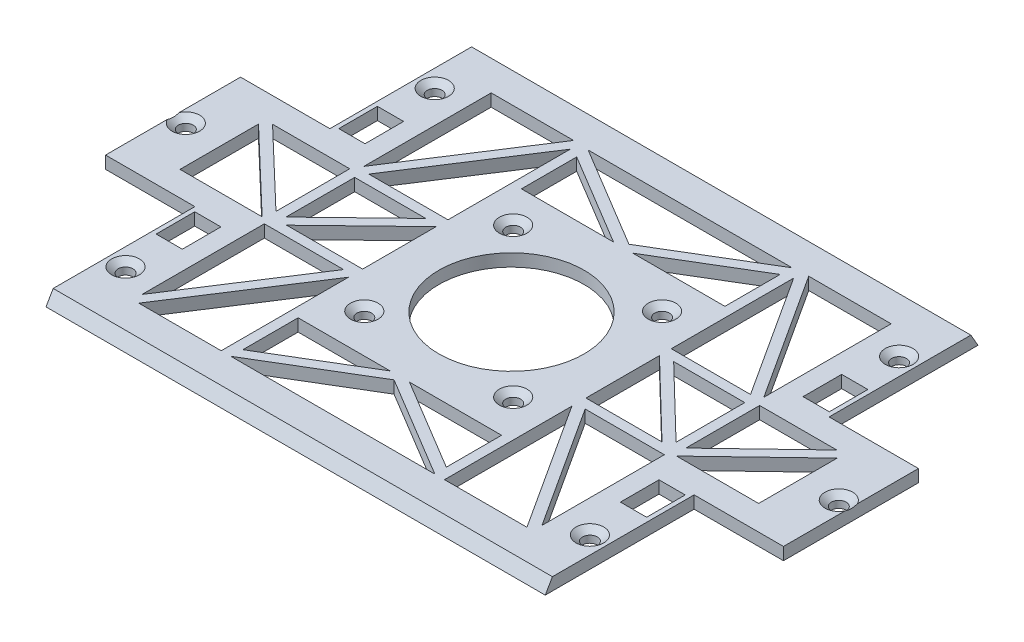
SolidWorks part; units mm, degrees
material "6061-T6 (SS)"
ref_plane "Front Plane" through (0, 0, 0) normal (0, 0, 1) x (1, 0, 0)
ref_plane "Top Plane" through (0, 0, 0) normal (0, 1, 0) x (1, 0, 0)
ref_plane "Right Plane" through (0, 0, 0) normal (1, 0, 0) x (0, 0, -1)
sketch "Sketch1" plane through (0, 0, 0) normal (0, 1, 0) x (1, 0, 0)
  line L0 (-65.4553, 70.6447) -> (62.3067, 70.6447)
  line L1 (62.3067, -40.0993) -> (-65.4553, -40.0993)
  line L2 (-65.4553, 70.6447) -> (-65.4553, 32.5447)
  line L4 (62.3067, 70.6447) -> (62.3067, 32.5447)
  line L9 (-65.4553, -1.9993) -> (-65.4553, -40.0993)
  line L11 (62.3067, 32.5447) -> (85.1667, 32.5447)
  line L13 (62.3067, -1.9993) -> (85.1667, -1.9993)
  line L14 (85.1667, 32.5447) -> (85.1667, -1.9993)
  line L15 (-65.4553, -1.9993) -> (-88.3153, -1.9993)
  line L17 (-65.4553, 32.5447) -> (-88.3153, 32.5447)
  line L18 (-88.3153, -1.9993) -> (-88.3153, 32.5447)
  line L19 (62.3067, -1.9993) -> (62.3067, -40.0993)
  circle A0 centre (-1.5743, 15.1457) radius 18.5801
  point P0 (0, 0)
  dimension "D5" = 63.881
  dimension "D7" = 62.3067
  dimension "D6" = 55.499
  dimension "D9" = 37.1602
  dimension "D1" = 127.762
  dimension "D2" = 38.1
  dimension "D3" = 34.544
  dimension "D4" = 22.86
  dimension "D8" = 15.1457
extrude "Boss-Extrude1" add sketch "Sketch1" along normal blind 3.175
ref_plane "Plane1" through (0, 0, -15.2727) normal (0, 0, 1) x (1, 0, 0)
hole_wizard "CSK for #6 Flat Head Machine Screw (100)1" positions "Sketch3" profile "Sketch2" countersink size "#6" standard "ANSI Inch" end condition through all
sketch "Sketch3" plane through (0, 3.175, 0) normal (0, 1, 0) x (1, 0, 0)
  point P0 (-60.9786, 54.8967)
  point P3 (-85.1086, 15.3362)
  point P6 (-60.9786, -24.2243)
  point P9 (57.8617, -24.2243)
  point P12 (81.9917, 15.3362)
  point P15 (57.8617, 54.8967)
  point P18 (-20.6085, 34.6084)
  point P21 (-20.6085, -3.4916)
  point P24 (17.4915, -3.4916)
  point P27 (17.4915, 34.6084)
sketch "Sketch2" plane through (-60.9786, 3.175, -54.8967) normal (1, 0, 0) x (0, 0, 1)
  line L0 (0, 0) -> (0, 3.175)
  line L1 (0, 3.175) -> (1.8986, 3.175)
  line L2 (1.8986, 3.175) -> (1.8986, 1.38)
  line L3 (1.8986, 1.38) -> (3.5433, 0)
  line L5 (3.5433, 0) -> (0, 0)
  line L6 (-1.8986, 1.38) -> (-3.5433, 0) construction
  line L11 (0, -6.35) -> (0, 107.95) construction
  dimension "Thru Hole Dia." = 3.7973
  dimension "Thru Hole Depth" = 3.175
  dimension "Near C'Sink Dia." = 7.0866
  dimension "Near C'Sink Angle" = 100
sketch "Sketch4" plane through (0, 0, 0) normal (1, 0, 0) x (0, 0, -1)
  line L0 (70.6447, 0) -> (68.8116, 3.175)
  line L2 (70.6447, 3.175) -> (32.5447, 3.175) construction
  line L4 (68.8116, 3.175) -> (70.6447, 3.175)
  line L6 (70.6447, 3.175) -> (70.6447, 0)
  line L7 (70.6447, 0) -> (32.5447, 0) construction
  dimension "D1" = 60
extrude "Cut-Extrude2" cut sketch "Sketch4" against normal through all and the other way through all
mirror "Mirror1" about plane through (0, 0, -15.2727) normal (0, 0, 1) of "Cut-Extrude2"
ref_plane "Plane2" through (-1.5743, 0, 0) normal (1, 0, 0) x (0, 0, -1)
sketch "Sketch7" plane through (0, 3.175, 0) normal (0, 1, 0) x (1, 0, 0)
  line L0 (-65.4553, 68.8116) -> (-65.4553, 32.5447) construction
  line L1 (-52.7553, 61.1197) -> (-30.1493, 61.1197)
  line L2 (-52.7553, 61.1197) -> (-52.7553, 26.1947)
  line L3 (-52.7553, -30.5743) -> (-30.1493, -30.5743)
  line L4 (-30.1493, 61.1197) -> (-30.1493, -30.5743)
  line L5 (-65.4553, -40.0993) -> (62.3067, -40.0993) construction
  line L6 (62.3067, 70.6447) -> (-65.4553, 70.6447) construction
  line L7 (-65.4553, 32.5447) -> (-88.3153, 32.5447) construction
  line L8 (-75.6153, 26.1947) -> (-52.7553, 26.1947)
  line L9 (-75.6153, 26.1947) -> (-75.6153, 4.3507)
  line L10 (-75.6153, 4.3507) -> (-52.7553, 4.3507)
  line L11 (-75.6153, 26.1947) -> (-52.7553, 4.3507) construction
  line L12 (-88.3153, -1.9993) -> (-65.4553, -1.9993) construction
  line L13 (-52.7553, 4.3507) -> (-52.7553, -30.5743)
  line L15 (-52.7553, -30.5743) -> (-30.1493, 4.3507) construction
  line L16 (-52.7553, 4.3507) -> (-52.7553, 26.1947) construction
  line L17 (-52.7553, 4.3507) -> (-30.1493, 26.1947) construction
  line L18 (-52.7553, 4.3507) -> (-30.1493, 4.3507) construction
  line L19 (-30.1493, 4.3507) -> (-29.4006, 1.9994)
  line L20 (-76.4927, 25.2765) -> (-53.6327, 3.4325)
  line L21 (-52.7553, 26.1947) -> (-30.1493, 61.1197) construction
  line L22 (-52.7553, 26.1947) -> (-30.1493, 26.1947) construction
  line L23 (-74.7379, 27.1129) -> (-51.8779, 5.2689)
  line L24 (-53.6378, 5.264) -> (-33.2913, 24.9247)
  line L25 (-52.7553, 24.9247) -> (-33.2913, 24.9247)
  line L26 (-53.8215, 26.8848) -> (-31.2155, 61.8098)
  line L27 (-54.0253, 4.3507) -> (-54.0253, 26.1947)
  line L28 (-53.8215, -29.8842) -> (-32.4842, 3.0807)
  line L29 (-52.7553, 3.0807) -> (-32.4842, 3.0807)
  line L30 (-51.8728, 3.4374) -> (-27.0074, 27.4647)
  line L31 (-52.7553, 27.4647) -> (-27.0074, 27.4647)
  line L32 (-51.6892, 25.5046) -> (-29.0832, 60.4296)
  line L33 (-51.4853, 4.3507) -> (-51.4853, 26.1947)
  line L34 (-51.6892, -31.2644) -> (-27.8145, 5.6207)
  line L35 (-52.7553, 5.6207) -> (-27.8145, 5.6207)
  line L36 (-1.5743, -38.2662) -> (-1.5743, 68.8116) construction
  line L37 (-30.1493, -13.4293) -> (-1.5743, -13.4293)
  line L38 (-30.1493, -13.4293) -> (-30.1493, -30.5743) construction
  line L39 (-30.1493, -30.5743) -> (-1.5743, -30.5743)
  line L40 (-1.5743, -13.4293) -> (-1.5743, -30.5743)
  line L41 (-65.4553, -38.2662) -> (62.3067, -38.2662) construction
  line L42 (-65.4553, 68.8116) -> (62.3067, 68.8116) construction
  line L43 (-20.1544, 15.1457) -> (17.0058, 15.1457) construction
  line L44 (-30.1493, -30.5743) -> (-1.5743, -13.4293) construction
  line L45 (-27.6809, -30.5743) -> (-0.9209, -14.5183)
  line L46 (-29.4959, -31.6633) -> (-0.9209, -14.5183) construction
  line L47 (-27.6093, -13.4293) -> (-27.6093, -30.5743)
  line L48 (-30.1493, -13.4293) -> (-30.1493, -30.5743)
  line L49 (-27.6093, -27.5693) -> (-4.0428, -13.4293)
  line L50 (-1.5743, 43.7207) -> (-1.5743, 60.8657)
  line L51 (-27.6093, 57.8606) -> (-4.0428, 43.7207)
  line L52 (-27.6809, 60.8657) -> (-0.9209, 44.8097)
  line L53 (-30.1493, 60.8657) -> (-1.5743, 60.8657)
  line L54 (-27.6093, 43.7207) -> (-27.6093, 60.8657)
  line L55 (-30.1493, 43.7207) -> (-1.5743, 43.7207)
  line L56 (-57.8036, -12.8616) -> (-57.8036, -3.3366) construction
  line L57 (-57.8036, -3.3366) -> (-64.1536, -3.3366) construction
  line L58 (-64.1536, -3.3366) -> (-64.1536, -12.8616) construction
  line L59 (-64.1536, -12.8616) -> (-57.8036, -12.8616) construction
  line L60 (-64.1536, 43.407) -> (-64.1536, 33.882) construction
  line L61 (-64.1536, 33.882) -> (-57.8036, 33.882) construction
  line L62 (-57.8036, 33.882) -> (-57.8036, 43.407) construction
  line L63 (-57.8036, 43.407) -> (-64.1536, 43.407) construction
  line L64 (-57.8036, -12.8616) -> (-57.8036, -3.3366) construction
  line L65 (-57.8036, -3.3366) -> (-64.1536, -3.3366) construction
  line L66 (-64.1536, -3.3366) -> (-64.1536, -12.8616) construction
  line L67 (-64.1536, -12.8616) -> (-57.8036, -12.8616) construction
  line L68 (-64.1536, 43.407) -> (-64.1536, 33.882) construction
  line L69 (-64.1536, 33.882) -> (-57.8036, 33.882) construction
  line L70 (-57.8036, 33.882) -> (-57.8036, 43.407) construction
  line L71 (-57.8036, 43.407) -> (-64.1536, 43.407) construction
  line L72 (-57.6258, -13.0394) -> (-57.6258, -3.1588)
  line L73 (-57.6258, -3.1588) -> (-64.3314, -3.1588)
  line L74 (-64.3314, -3.1588) -> (-64.3314, -13.0394)
  line L75 (-64.3314, -13.0394) -> (-57.6258, -13.0394)
  line L76 (-64.3314, 43.5848) -> (-64.3314, 33.7042)
  line L77 (-64.3314, 33.7042) -> (-57.6258, 33.7042)
  line L78 (-57.6258, 33.7042) -> (-57.6258, 43.5848)
  line L79 (-57.6258, 43.5848) -> (-64.3314, 43.5848)
  circle A0 centre (-1.5743, 15.1457) radius 18.5801 construction
  circle A1 centre (-1.5743, 15.1457) radius 18.5801 construction
  dimension "D1" = 28.575
  dimension "D2" = 12.7
  dimension "D3" = 9.525
  dimension "D4" = 9.525
  dimension "D5" = 12.7
  dimension "D6" = 6.35
  dimension "D7" = 6.35
  dimension "D12" = 28.575
  dimension "D14" = 2.54
  dimension "D8" = 1.27
  dimension "D9" = 1.27
  dimension "D10" = 1.27
  dimension "D11" = 1.27
  dimension "D13" = 1.27
  dimension "D15" = 2.54
  dimension "D16" = 0.1778
  dimension "D17" = 0.1778
extrude "Cut-Extrude5" cut sketch "Sketch7" against normal through all contours L23 L27 L8 | L20 L9 L10 | L33 L24 L25 | L32 L31 L4 | L2 L26 L1 | L30 L35 L4 | L29 L13 L28 | L34 L3 L4 | L54 L55 L51 | L53 L52 L50 | L47 L49 L37 | L45 L39 L40 | L66 L67 L64 L65 | L70 L71 L68 L69 | L78 L79 L76 L77 | L74 L75 L72 L73
ref_plane "Plane3" through (-1.5743, 0, 0) normal (1, 0, 0) x (0, 0, -1)
mirror "Mirror3" about plane through (-1.5743, 0, 0) normal (1, 0, 0) of "Cut-Extrude5"
equation "\"D5@Sketch1\"=\"D1@Sketch1\"/2"
